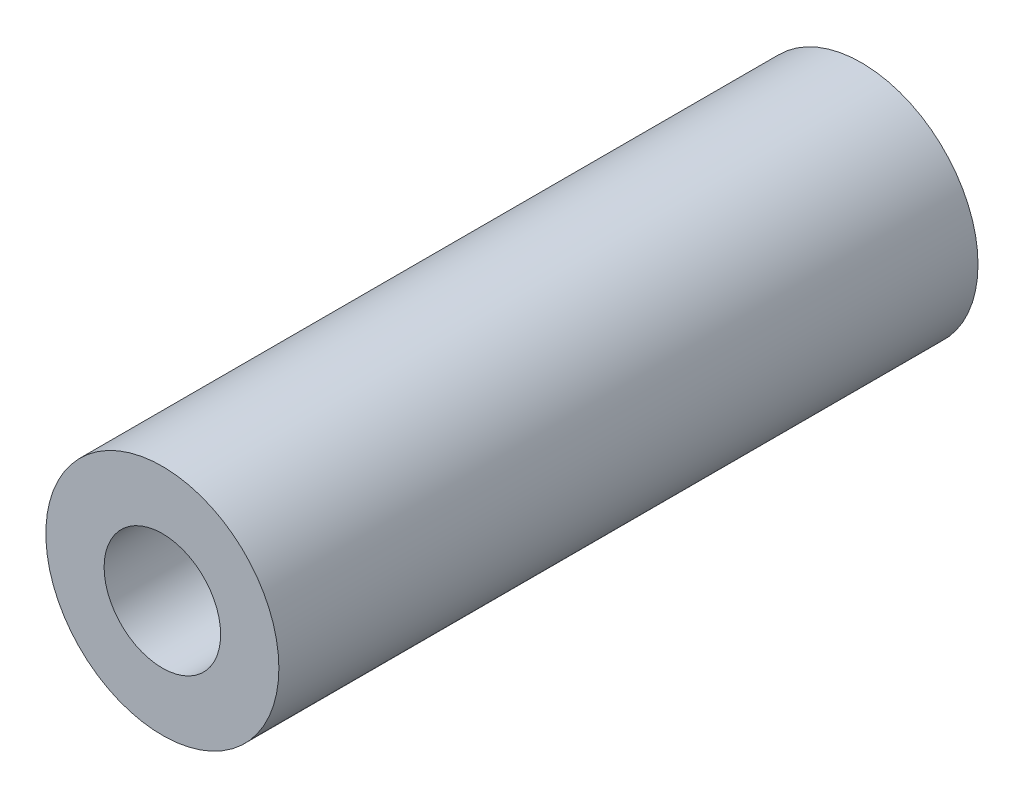
SolidWorks part; units mm, degrees
ref_plane "Plan de face" through (0, 0, 0) normal (0, 0, 1) x (1, 0, 0)
ref_plane "Plan de dessus" through (0, 0, 0) normal (0, 1, 0) x (1, 0, 0)
ref_plane "Plan de droite" through (0, 0, 0) normal (1, 0, 0) x (0, 0, -1)
sketch "Esquisse1" plane through (0, 0, 0) normal (0, 0, 1) x (1, 0, 0)
  circle A0 centre (0, 0) radius 5
  dimension "D1" = 10
extrude "Boss.-Extru.1" add sketch "Esquisse1" along normal blind 30
sketch "Esquisse2" plane through (0, 0, 0) normal (0, 0, -1) x (-1, 0, 0)
  circle A0 centre (0, 0) radius 2.5
  dimension "D1" = 5
extrude "Enlèv. mat.-Extru.1" cut sketch "Esquisse2" against normal up to next
